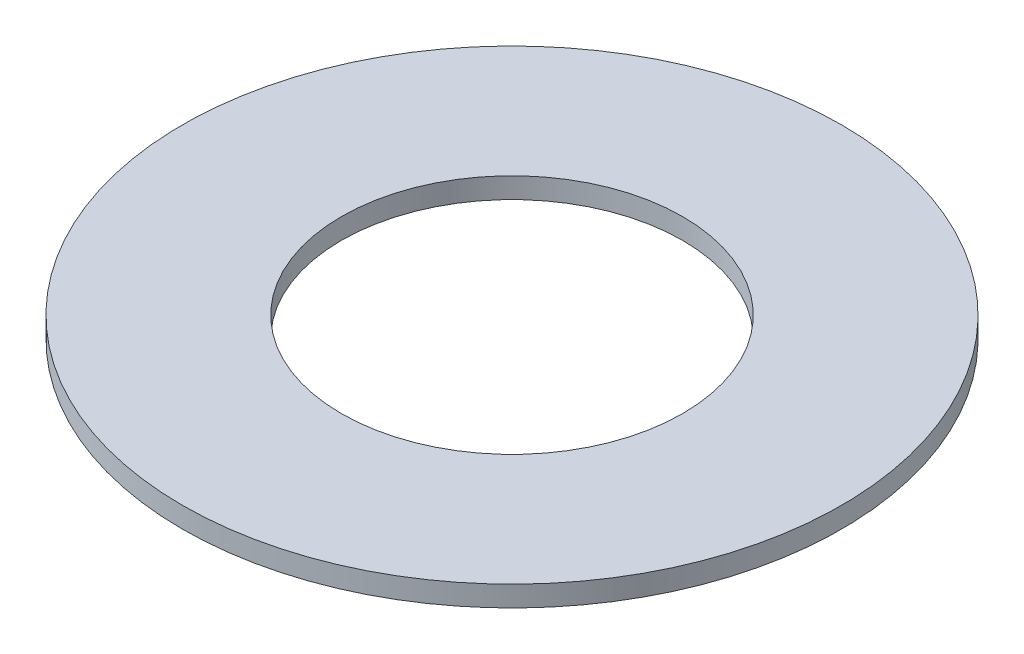
SolidWorks part; units mm, degrees
ref_plane "Front Plane" through (0, 0, 0) normal (0, 0, 1) x (1, 0, 0)
ref_plane "Top Plane" through (0, 0, 0) normal (0, 1, 0) x (1, 0, 0)
ref_plane "Right Plane" through (0, 0, 0) normal (1, 0, 0) x (0, 0, -1)
sketch "Sketch1" plane through (0, 0, 0) normal (0, 1, 0) x (1, 0, 0)
  circle A0 centre (0, 0) radius 76
  circle A1 centre (0, 0) radius 39.35
extrude "Boss-Extrude1" add sketch "Sketch1" along normal blind 4.76
